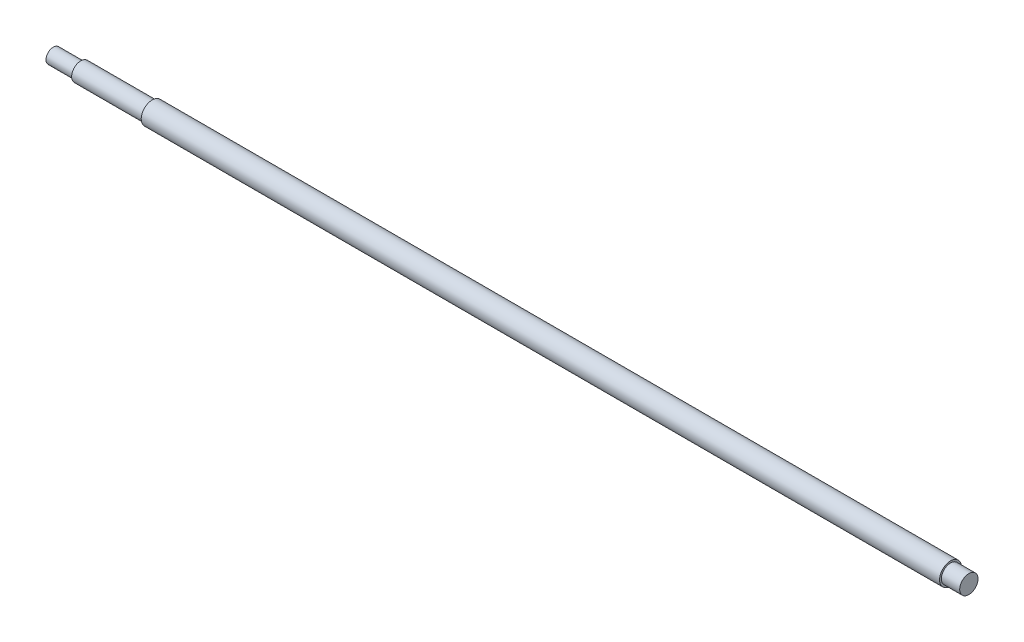
SolidWorks part; units mm, degrees
ref_plane "Спереди" through (0, 0, 0) normal (0, 0, 1) x (1, 0, 0)
ref_plane "Сверху" through (0, 0, 0) normal (0, 1, 0) x (1, 0, 0)
ref_plane "Справа" through (0, 0, 0) normal (1, 0, 0) x (0, 0, -1)
sketch "Эскиз1" plane through (0, 0, 0) normal (0, 0, 1) x (1, 0, 0)
  line L0 (0, 0) -> (-500, 0) construction
  line L1 (0, 0) -> (0, 5)
  line L2 (0, 5) -> (-10, 5)
  line L3 (-10, 5) -> (-10, 6)
  line L4 (-10, 6) -> (-446, 6)
  line L5 (-446, 6) -> (-446, 5)
  line L6 (-446, 5) -> (-485, 5)
  line L7 (-485, 5) -> (-485, 4)
  line L8 (-485, 4) -> (-500, 4)
  line L9 (-500, 4) -> (-500, 0)
  line L10 (0, 0) -> (-500, 0)
  point P1 (0, 2.5)
  point P3 (0, 0)
  dimension "D1" = 10
  dimension "D2" = 39
  dimension "D3" = 15
  dimension "D4" = 4
  dimension "D5" = 5
  dimension "D6" = 6
  dimension "D7" = 5
  dimension "D8" = 500
revolve "Повернуть1" add sketch "Эскиз1" angle 360 about L0
